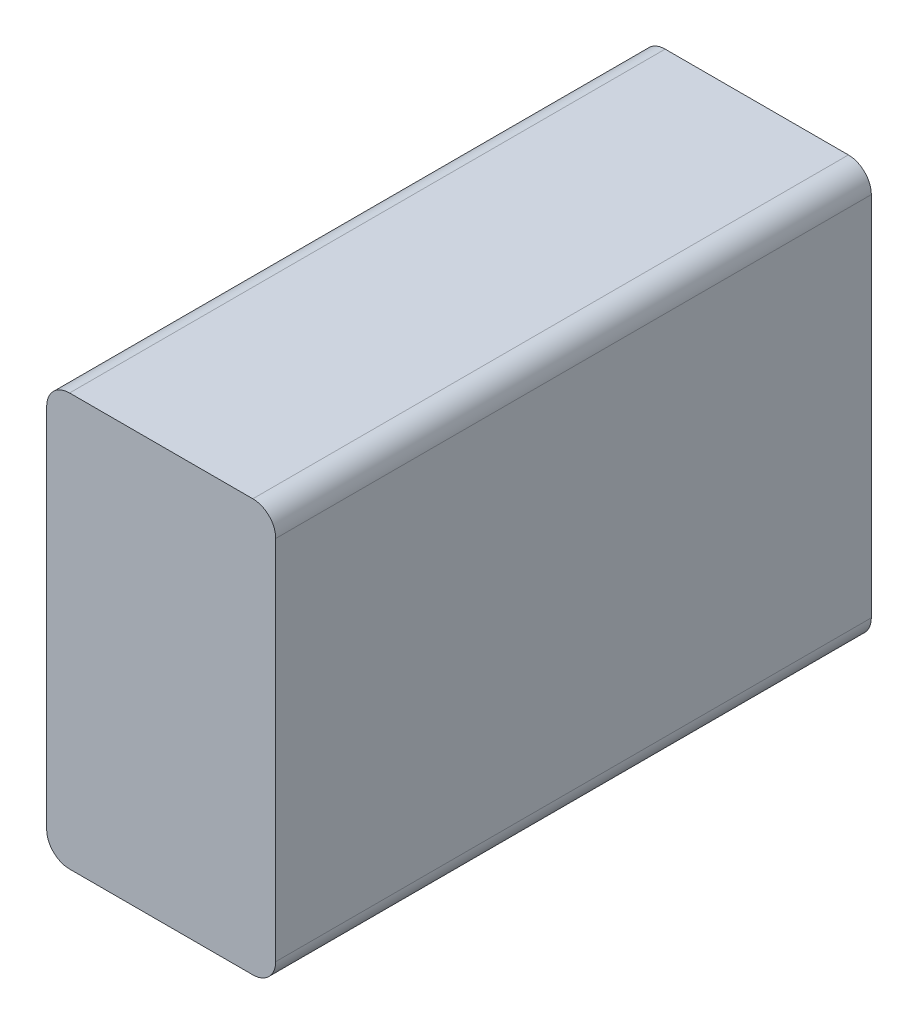
SolidWorks part; units mm, degrees
ref_plane "Front Plane" through (0, 0, 0) normal (0, 0, 1) x (1, 0, 0)
ref_plane "Top Plane" through (0, 0, 0) normal (0, 1, 0) x (1, 0, 0)
ref_plane "Right Plane" through (0, 0, 0) normal (1, 0, 0) x (0, 0, -1)
sketch "Sketch2" plane through (0, 0, 0) normal (0, 0, 1) x (1, 0, 0)
  line L0 (-57.1527, 9.6415) -> (-57.1527, -32.69) construction
  line L1 (-35.9244, 1.9853) -> (0.0786, 1.9853) construction
  line L2 (-53.1527, 10.9853) -> (-61.1527, 10.9853)
  line L3 (-62.1527, 9.9853) -> (-62.1527, -6.0147)
  line L4 (-52.1527, 9.9853) -> (-52.1527, -6.0147)
  line L5 (-53.1527, -7.0147) -> (-61.1527, -7.0147)
  arc A0 (-62.1527, 9.9853) -> (-61.1527, 10.9853) centre (-61.1527, 9.9853) cw
  arc A1 (-52.1527, 9.9853) -> (-53.1527, 10.9853) centre (-53.1527, 9.9853) ccw
  arc A2 (-52.1527, -6.0147) -> (-53.1527, -7.0147) centre (-53.1527, -6.0147) cw
  arc A3 (-62.1527, -6.0147) -> (-61.1527, -7.0147) centre (-61.1527, -6.0147) ccw
  point P11 (-62.1527, 1.9853)
  point P12 (-57.1527, 10.9853)
  point P18 (-57.1527, -7.0147)
  point P19 (-52.1527, 1.9853)
  dimension "D1" = 1
  dimension "D2" = 18
  dimension "D3" = 10
extrude "Boss-Extrude1" add sketch "Sketch2" along normal blind 26
